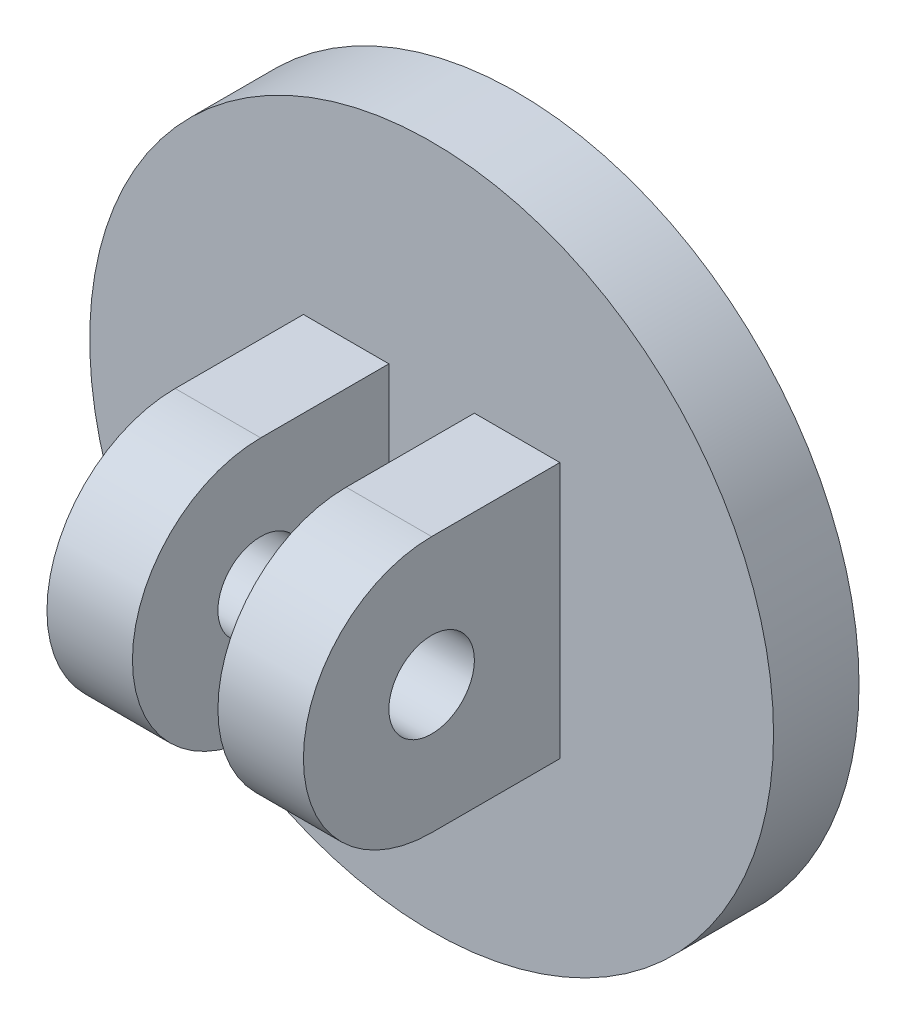
SolidWorks part; units mm, degrees
ref_plane "Alzado" through (0, 0, 0) normal (0, 0, 1) x (1, 0, 0)
ref_plane "Planta" through (0, 0, 0) normal (0, 1, 0) x (1, 0, 0)
ref_plane "Vista lateral" through (0, 0, 0) normal (1, 0, 0) x (0, 0, -1)
sketch "Croquis1" plane through (0, 0, 0) normal (0, 0, 1) x (1, 0, 0)
  circle A0 centre (0, 0) radius 20
  dimension "D1" = 40
extrude "Saliente-Extruir1" add sketch "Croquis1" along normal blind 5
sketch "Croquis2" plane through (0, 0, 5) normal (0, 0, 1) x (1, 0, 0)
  circle A0 centre (0, 0) radius 2.5
  dimension "D1" = 5
extrude "Cortar-Extruir1" cut sketch "Croquis2" against normal blind 5
sketch "Croquis3" plane through (0, 0, 5) normal (0, 0, 1) x (1, 0, 0)
  line L1 (-2.5, 19.8431) -> (2.5, 19.8431) construction
  line L2 (-2.5, 19.8431) -> (-2.5, -19.8431) construction
  line L3 (-2.5, -19.8431) -> (2.5, -19.8431) construction
  line L4 (2.5, 19.8431) -> (2.5, -19.8431) construction
  line L5 (-2.5, 19.8431) -> (2.5, -19.8431) construction
  line L6 (-2.5, -19.8431) -> (2.5, 19.8431) construction
  line L7 (2.5, -7.5) -> (7.5, -7.5)
  line L8 (2.5, -7.5) -> (2.5, 7.5)
  line L9 (2.5, 7.5) -> (7.5, 7.5)
  line L10 (7.5, -7.5) -> (7.5, 7.5)
  circle A0 centre (0, 0) radius 20 construction
  circle A1 centre (0, 0) radius 2.5 construction
  point P0 (0, 0)
  point P14 (5, -7.5)
  point P15 (5, 7.5)
  dimension "D1" = 7.5
  dimension "D2" = 15
  dimension "D3" = 5
extrude "Saliente-Extruir3" add sketch "Croquis3" along normal blind 15
sketch "Croquis4" plane through (7.5, 0, 0) normal (1, 0, 0) x (0, 0, -1)
  line L0 (-20, -7.5) -> (-20, 7.5) construction
  line L1 (-20, 7.5) -> (-5, 7.5) construction
  line L2 (-20, -7.5) -> (-5, -7.5) construction
  circle A0 centre (-12.5, 0) radius 2.5
  arc A1 (-12.5, 7.5) -> (-12.5, -7.5) centre (-12.5, 0) ccw
  line M2 (-5, 7.5) -> (-20, 7.5)
  line M3 (-20, 7.5) -> (-20, -7.5)
  line M4 (-20, -7.5) -> (-5, -7.5)
  dimension "D1" = 5
  dimension "D2" = 7.5
  dimension "D3" = 7.5
extrude "Cortar-Extruir2" cut sketch "Croquis4" against normal blind 5 contours A1 M3 M4 | A1 M2 M3 | A0
mirror "Simetría1" about plane through (0, 0, 0) normal (1, 0, 0) of bodies 107
